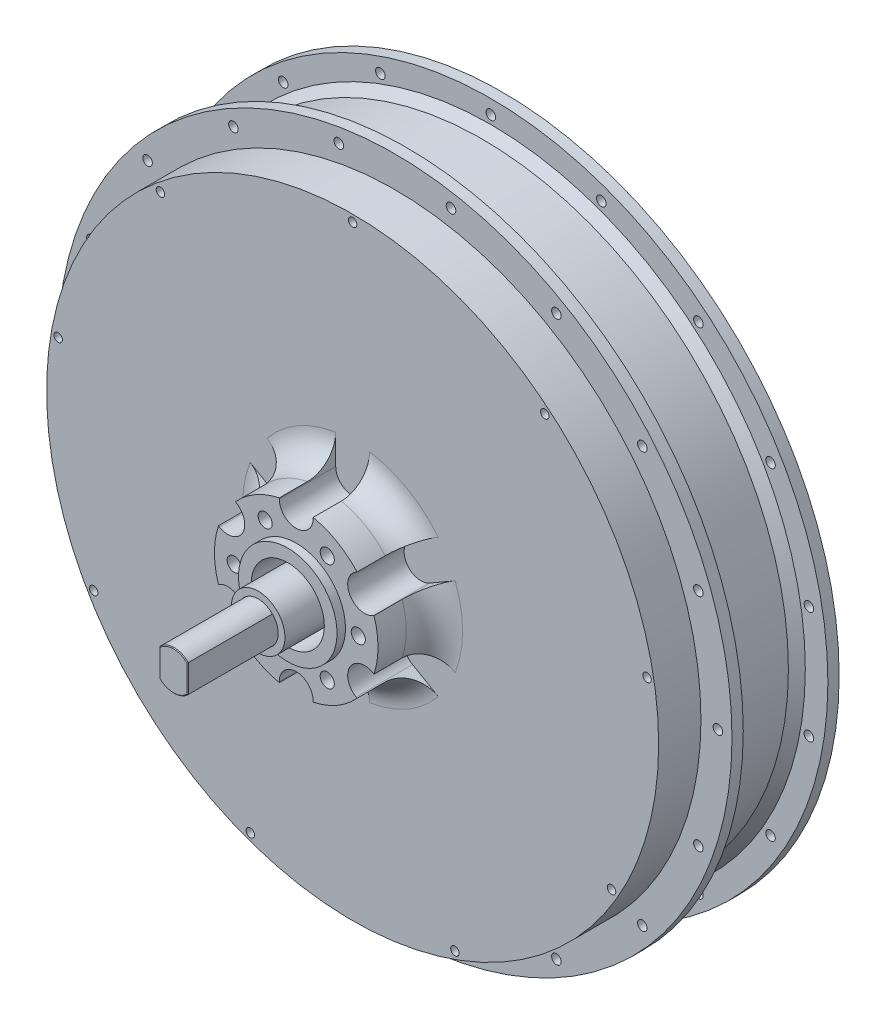
SolidWorks part; units mm, degrees
ref_plane "Front Plane" through (0, 0, 0) normal (0, 0, 1) x (1, 0, 0)
ref_plane "Top Plane" through (0, 0, 0) normal (0, 1, 0) x (1, 0, 0)
ref_plane "Right Plane" through (0, 0, 0) normal (1, 0, 0) x (0, 0, -1)
sketch "Sketch1" plane through (0, 0, 0) normal (0, 0, 1) x (1, 0, 0)
  line L0 (-22.4342, 24.8051) -> (-22.4342, 12.8051) construction
  line L3 (-27.4342, 18.8051) -> (-17.4342, 18.8051) construction
  line L4 (-27.4342, 23.7041) -> (-27.4342, 13.9062)
  line L5 (-17.4342, 23.7041) -> (-17.4342, 13.9062)
  arc A0 (-27.4342, 15.4885) -> (-17.4342, 15.4885) centre (-22.4342, 18.8051) ccw construction
  arc A1 (-17.4342, 22.1218) -> (-27.4342, 22.1218) centre (-22.4342, 18.8051) ccw construction
  arc A2 (-27.4342, 13.9062) -> (-17.4342, 13.9062) centre (-22.4342, 18.8051) ccw
  arc A3 (-17.4342, 23.7041) -> (-27.4342, 23.7041) centre (-22.4342, 18.8051) ccw
  dimension "D1" = 6
extrude "Extrude1" add sketch "Sketch1" against normal blind 195
chamfer "Chamfer1" distance 0.25 angle 45 8 edges at (-22.4342, 11.8051, -195) (-27.4342, 18.8051, -195) (-17.4342, 18.8051, -195) (-22.4342, 25.8051, -195) (-22.4342, 11.8051, 0) (-27.4342, 18.8051, 0) (-17.4342, 18.8051, 0) (-22.4342, 25.8051, 0)
ref_plane "Plane17" through (0, 0, -97.5) normal (0, 0, 1) x (1, 0, 0)
sketch "Sketch18" plane through (0, 0, -97.5) normal (0, 0, 1) x (1, 0, 0)
  line L0 (-22.4342, 25.8051) -> (-22.4342, 11.8051) construction
  line L1 (-27.4342, 18.8051) -> (-17.4342, 18.8051) construction
  line L2 (-27.4342, 13.9062) -> (-27.4342, 23.7041) construction
  line L3 (-17.4342, 23.7041) -> (-17.4342, 13.9062) construction
  arc A0 (-17.4342, 23.7041) -> (-27.4342, 23.7041) centre (-22.4342, 18.8051) ccw construction
  arc A1 (-27.4342, 13.9062) -> (-17.4342, 13.9062) centre (-22.4342, 18.8051) ccw construction
ref_plane "Plane1" through (0, 0, -165) normal (0, 0, -1) x (-1, 0, 0)
sketch "Sketch2" plane through (0, 0, -165) normal (0, 0, -1) x (-1, 0, 0)
  circle A0 centre (22.4342, 18.8051) radius 7.1
  circle A1 centre (22.4342, 18.8051) radius 6.15 construction
  circle A2 centre (22.4342, 18.8051) radius 9.5
  dimension "D1" = 14.2
  dimension "D2" = 19
extrude "Extrude2" add sketch "Sketch2" against normal blind 33.5 separate body
ref_plane "Plane2" through (0, 0, -131.5) normal (0, 0, 1) x (1, 0, 0)
sketch "Sketch3" plane through (0, 0, -131.5) normal (0, 0, 1) x (1, 0, 0)
  circle A0 centre (-22.4342, 18.8051) radius 17.4625
  circle A1 centre (-22.4342, 18.8051) radius 7.1
  dimension "D1" = 34.925
extrude "Extrude3" add sketch "Sketch3" against normal blind 12
ref_plane "Plane4" through (-22.4342, 0, 0) normal (1, 0, 0) x (0, 0, -1)
sketch "Sketch5" plane through (-22.4342, 0, 0) normal (1, 0, 0) x (0, 0, -1)
  line L0 (0, 18.8051) -> (195, 18.8051) construction
  line L1 (109.5, 127.3051) -> (112.5, 130.3051)
  line L2 (78.5, 138.3051) -> (78.5, 127.3051)
  line L3 (131.5, 25.9051) -> (131.5, 50.8051)
  line L4 (120.5, 18.8051) -> (120.5, 50.8051) construction
  line L5 (131.5, 50.8051) -> (131.25, 50.8051)
  line L6 (0, 14.0093) -> (0, 23.601) construction
  line L7 (195, 23.601) -> (195, 14.0093) construction
  line L8 (127.5, 50.8051) -> (127.5, 54.8051) construction
  line L9 (127.5, 18.8051) -> (127.5, 50.8051) construction
  line L11 (63.5, 18.8051) -> (131.5, 18.8051) construction
  line L12 (82.5, 130.3051) -> (82.5, 138.3051)
  line L13 (82.5, 138.3051) -> (78.5, 138.3051)
  line L14 (85.5, 127.3051) -> (82.5, 130.3051)
  line L16 (123.5, 58.5551) -> (123.5, 127.3051)
  line L17 (116.5, 130.2648) -> (116.5, 18.8051) construction
  line L18 (63.5, 127.3051) -> (78.5, 127.3051)
  line L20 (116.5, 138.3051) -> (116.5, 127.3051)
  line L22 (116.5, 127.3051) -> (123.5, 127.3051)
  line L23 (97.5, 18.8051) -> (97.5, 127.3051) construction
  line L24 (63.5, 127.3051) -> (63.5, 57.8051)
  line L27 (63.5, 25.9051) -> (131.5, 25.9051)
  line L28 (131.5, 50.8051) -> (63.5, 50.8051) construction
  line L29 (63.5, 25.9051) -> (63.5, 57.8051) construction
  line L31 (78.5, 130.3051) -> (78.5, 18.8051) construction
  line L32 (43.5, 47.8051) -> (53.5, 47.8051)
  line L33 (123.5, 58.5551) -> (78.5, 58.5551) construction
  line L36 (43.5, 31.7701) -> (63.5, 31.7701)
  line L37 (40.5, 36.2701) -> (40.5, 31.7701)
  line L38 (43.5, 31.7701) -> (40.5, 31.7701)
  line L39 (165, 18.8051) -> (165, 31.995) construction
  line L40 (165, 9.3051) -> (165, 28.3051) construction
  line L41 (85.5, 127.3051) -> (109.5, 127.3051)
  line L42 (143.5, 18.8051) -> (143.5, 40.2887) construction
  line L43 (143.5, 9.3051) -> (143.5, 28.3051) construction
  line L44 (112.5, 130.3051) -> (112.5, 138.3051)
  line L45 (112.5, 138.3051) -> (116.5, 138.3051)
  line L47 (43.5, 36.2701) -> (43.5, 31.7701) construction
  line L48 (43.5, 36.2701) -> (131.5, 36.2701) construction
  line L49 (43.5, 36.2701) -> (43.5, 47.8051)
  line L50 (63.5, 25.9051) -> (63.5, 31.7701)
  line L51 (40.5, 36.2701) -> (43.5, 36.2701)
  arc A0 (131.25, 50.8051) -> (123.5, 58.5551) centre (131.25, 58.5551) cw
  arc A1 (63.5, 57.8051) -> (53.5, 47.8051) centre (53.5, 57.8051) cw
  point P57 (82.5, 127.3051)
  point P58 (112.5, 127.3051)
  dimension "D12" = 23
  dimension "D20" = 4
  dimension "D8" = 7.75
  dimension "D13" = 10
  dimension "D10" = 15
  dimension "D3" = 195
  dimension "D4" = 4
  dimension "D5" = 11
  dimension "D6" = 11
  dimension "D7" = 97.5
  dimension "D9" = 30
  dimension "D11" = 12.965
  dimension "D14" = 21.5
  dimension "D16" = 119.5
  dimension "D18" = 30
  dimension "D19" = 108.5
revolve "Revolve1" add sketch "Sketch5" angle 360 about L0
ref_plane "Plane5" through (0, 0, -116.5) normal (0, 0, -1) x (-1, 0, 0)
sketch "Sketch6" plane through (0, 0, -116.5) normal (0, 0, -1) x (-1, 0, 0)
  line L0 (22.4342, 18.8051) -> (22.4342, 133.3051) construction
  circle A0 centre (22.4342, 18.8051) radius 6.15 construction
  circle A1 centre (61.5955, 126.3999) radius 1.7
  circle A2 centre (22.4342, 18.3051) radius 120 construction
  circle A3 centre (22.4342, 133.3051) radius 1.7
  circle A4 centre (96.0334, 106.5172) radius 1.7
  circle A5 centre (121.5941, 76.0551) radius 1.7
  circle A6 centre (135.1947, 38.6878) radius 1.7
  circle A7 centre (135.1947, -1.0776) radius 1.7
  circle A8 centre (121.5941, -38.4449) radius 1.7
  circle A9 centre (96.0334, -68.907) radius 1.7
  circle A10 centre (61.5955, -88.7897) radius 1.7
  circle A11 centre (22.4342, -95.6949) radius 1.7
  circle A12 centre (-16.7271, -88.7897) radius 1.7
  circle A13 centre (-51.165, -68.907) radius 1.7
  circle A14 centre (-76.7257, -38.4449) radius 1.7
  circle A15 centre (-90.3263, -1.0776) radius 1.7
  circle A16 centre (-90.3263, 38.6878) radius 1.7
  circle A17 centre (-76.7257, 76.0551) radius 1.7
  circle A18 centre (-51.165, 106.5172) radius 1.7
  circle A19 centre (-16.7271, 126.3999) radius 1.7
  circle A21 centre (22.4342, 18.8051) radius 114.5 construction
  dimension "D1" = 18
  dimension "D2" = 229
extrude "Extrude5" cut sketch "Sketch6" against normal blind 4
ref_plane "Plane6" through (0, 0, -78.5) normal (0, 0, 1) x (1, 0, 0)
sketch "Sketch7" plane through (0, 0, -78.5) normal (0, 0, 1) x (1, 0, 0)
  line L0 (-22.4342, 18.8051) -> (-22.4342, 133.3051) construction
  line L1 (-22.4342, 18.8051) -> (-42.3169, 131.5656) construction
  circle A0 centre (-2.5515, 131.5656) radius 1.7
  circle A1 centre (34.8158, 117.965) radius 1.7
  circle A2 centre (65.2779, 92.4043) radius 1.7
  circle A3 centre (85.1606, 57.9664) radius 1.7
  circle A4 centre (92.0658, 18.8051) radius 1.7
  circle A5 centre (85.1606, -20.3562) radius 1.7
  circle A6 centre (65.2779, -54.794) radius 1.7
  circle A7 centre (34.8158, -80.3548) radius 1.7
  circle A8 centre (-2.5515, -93.9554) radius 1.7
  circle A9 centre (-42.3169, -93.9554) radius 1.7
  circle A10 centre (-79.6842, -80.3548) radius 1.7
  circle A11 centre (-110.1463, -54.794) radius 1.7
  circle A12 centre (-130.029, -20.3562) radius 1.7
  circle A13 centre (-136.9342, 18.8051) radius 1.7
  circle A14 centre (-130.029, 57.9664) radius 1.7
  circle A15 centre (-110.1463, 92.4043) radius 1.7
  circle A16 centre (-79.6842, 117.965) radius 1.7
  circle A17 centre (-22.4342, 18.8051) radius 114.5 construction
  circle A19 centre (-42.3169, 131.5656) radius 1.7
  dimension "D1" = 229
  dimension "D3" = 10
  dimension "D2" = 18
extrude "Extrude6" cut sketch "Sketch7" against normal blind 4
ref_plane "Plane18" through (0, 0, -30) normal (0, 0, 1) x (1, 0, 0)
sketch "Sketch19" plane through (0, 0, -30) normal (0, 0, 1) x (1, 0, 0)
  circle A3 centre (-22.4342, 18.8051) radius 9.5
  circle A4 centre (-22.4342, 18.8051) radius 6.15 construction
  circle A5 centre (-22.4342, 18.8051) radius 7.1
  dimension "D3" = 14.2
  dimension "D4" = 19
extrude "Extrude20" add sketch "Sketch19" against normal blind 30
ref_plane "Plane13" through (0, 0, -63.5) normal (0, 0, 1) x (1, 0, 0)
sketch "Sketch14" plane through (0, 0, -63.5) normal (0, 0, 1) x (1, 0, 0)
  line L1 (-22.4342, 18.8051) -> (-22.4342, 124.8051) construction
  circle A0 centre (-22.4342, 18.8051) radius 106 construction
  circle A1 centre (45.7013, 100.0058) radius 1.5
  circle A2 centre (-22.4342, 124.8051) radius 1.5
  circle A3 centre (81.9554, 37.2118) radius 1.5
  circle A4 centre (69.3645, -34.1949) radius 1.5
  circle A5 centre (13.8199, -80.8023) radius 1.5
  circle A6 centre (-58.6883, -80.8023) radius 1.5
  circle A7 centre (-114.2329, -34.1949) radius 1.5
  circle A8 centre (-126.8238, 37.2118) radius 1.5
  circle A9 centre (-90.5697, 100.0058) radius 1.5
extrude "Extrude21" cut sketch "Sketch14" against normal blind 10
ref_plane "Plane19" through (0, 0, -123.5) normal (0, 0, -1) x (-1, 0, 0)
sketch "Sketch20" plane through (0, 0, -123.5) normal (0, 0, -1) x (-1, 0, 0)
  line L1 (22.4342, 18.8051) -> (-46.9869, 101.5379) construction
  line L3 (22.4342, 18.8051) -> (-13.8199, 118.4126) construction
  circle A0 centre (22.4342, 18.8051) radius 106 construction
  circle A1 centre (-13.8199, 118.4126) radius 1.5
  circle A2 centre (58.6883, 118.4126) radius 1.5
  circle A3 centre (114.2329, 71.8051) radius 1.5
  circle A4 centre (126.8238, 0.3984) radius 1.5
  circle A5 centre (90.5697, -62.3956) radius 1.5
  circle A6 centre (22.4342, -87.1949) radius 1.5
  circle A7 centre (-45.7013, -62.3956) radius 1.5
  circle A8 centre (-81.9554, 0.3984) radius 1.5
  circle A9 centre (-69.3645, 71.8051) radius 1.5
  dimension "D2" = 20
extrude "Extrude22" cut sketch "Sketch20" against normal blind 10
ref_plane "Plane20" through (0, 0, -63.5) normal (0, 0, 1) x (1, 0, 0)
sketch "Sketch21" plane through (0, 0, -63.5) normal (0, 0, 1) x (1, 0, 0)
  line L0 (-22.4342, 18.8051) -> (-22.4342, 40.8051) construction
  line L2 (-2.2776, 15.0688) -> (-0.7538, 15.0688) construction
  line L3 (-9.1201, 34.3931) -> (-8.3582, 35.7127) construction
  line L4 (-15.5917, 38.1295) -> (-14.8298, 39.4491) construction
  line L5 (-2.2776, 22.5415) -> (-0.7538, 22.5415) construction
  line L6 (-15.5917, -0.5192) -> (-14.8298, -1.8388) construction
  line L7 (-9.1201, 3.2172) -> (-8.3582, 1.8975) construction
  line L8 (-35.7483, 3.2172) -> (-36.5102, 1.8975) construction
  line L9 (-29.2767, -0.5192) -> (-30.0386, -1.8388) construction
  line L10 (-42.5908, 22.5415) -> (-44.1146, 22.5415) construction
  line L11 (-42.5908, 15.0688) -> (-44.1146, 15.0688) construction
  line L12 (-29.2767, 38.1295) -> (-30.0386, 39.4491) construction
  line L13 (-22.4342, 18.8051) -> (-11.4342, 37.8577) construction
  line L14 (-35.7483, 34.3931) -> (-36.5102, 35.7127) construction
  circle A0 centre (-22.4342, 18.8051) radius 22 construction
  arc A1 (-0.7538, 15.0688) -> (-0.7538, 22.5415) centre (-0.4342, 18.8051) ccw construction
  arc A2 (-8.3582, 35.7127) -> (-14.8298, 39.4491) centre (-11.4342, 37.8577) ccw construction
  circle A3 centre (-0.4342, 18.8051) radius 2.5 construction
  arc A4 (-14.8298, -1.8388) -> (-8.3582, 1.8975) centre (-11.4342, -0.2474) ccw construction
  circle A5 centre (-11.4342, -0.2474) radius 2.5 construction
  arc A6 (-36.5102, 1.8975) -> (-30.0386, -1.8388) centre (-33.4342, -0.2474) ccw construction
  circle A7 centre (-33.4342, -0.2474) radius 2.5 construction
  arc A8 (-44.1146, 22.5415) -> (-44.1146, 15.0688) centre (-44.4342, 18.8051) ccw construction
  circle A9 centre (-44.4342, 18.8051) radius 2.5 construction
  arc A10 (-30.0386, 39.4491) -> (-36.5102, 35.7127) centre (-33.4342, 37.8577) ccw construction
  circle A11 centre (-33.4342, 37.8577) radius 2.5 construction
  arc A12 (-35.7483, 34.3931) -> (-42.5908, 22.5415) centre (-22.4342, 18.8051) ccw construction
  arc A13 (-15.5917, 38.1295) -> (-29.2767, 38.1295) centre (-22.4342, 18.8051) ccw construction
  arc A14 (-2.2776, 22.5415) -> (-9.1201, 34.3931) centre (-22.4342, 18.8051) ccw construction
  arc A15 (-9.1201, 3.2172) -> (-2.2776, 15.0688) centre (-22.4342, 18.8051) ccw construction
  circle A16 centre (-11.4342, 37.8577) radius 2.5 construction
  arc A17 (-29.2767, -0.5192) -> (-15.5917, -0.5192) centre (-22.4342, 18.8051) ccw construction
  arc A18 (-42.5908, 15.0688) -> (-35.7483, 3.2172) centre (-22.4342, 18.8051) ccw construction
  circle A19 centre (-22.4342, 18.8051) radius 22 construction
  dimension "D1" = 44
  dimension "D2" = 30
ref_plane "Plane21" through (0, 0, -63.5) normal (0, 0, 1) x (1, 0, 0)
sketch "Sketch22" plane through (0, 0, -63.5) normal (0, 0, 1) x (1, 0, 0)
  line L0 (-22.4342, 18.8051) -> (-22.4342, 138.3051) construction
  line L1 (-22.4342, 33.8051) -> (-22.4342, 40.8051) construction
  line L2 (-1.1855, 38.0013) -> (8.5959, 43.6486)
  line L3 (4.8145, 27.609) -> (14.5959, 33.2563)
  line L4 (4.8145, 10.0013) -> (14.5959, 4.354)
  line L5 (-1.1855, -0.391) -> (8.5959, -6.0383)
  line L6 (-16.4342, -9.1949) -> (-16.4342, -20.4894)
  line L7 (-28.4342, -9.1949) -> (-28.4342, -20.4894)
  line L8 (-43.6829, -0.391) -> (-53.4643, -6.0383)
  line L9 (-49.6829, 10.0013) -> (-59.4643, 4.354)
  line L10 (-49.6829, 27.609) -> (-59.4643, 33.2563)
  line L11 (-43.6829, 38.0013) -> (-53.4643, 43.6486)
  line L13 (-28.4342, 46.8051) -> (-28.4342, 58.0997)
  line L14 (-16.4342, 46.8051) -> (-16.4342, 58.0997)
  circle A1 centre (-22.4342, 18.8051) radius 15 construction
  arc A2 (-16.4342, 58.0997) -> (-28.4342, 58.0997) centre (-22.4342, 18.8051) ccw
  arc A3 (14.5959, 33.2563) -> (8.5959, 43.6486) centre (-22.4342, 18.8051) ccw
  circle A4 centre (-22.4342, 18.8051) radius 17.465 construction
  arc A5 (-1.1855, 38.0013) -> (4.8145, 27.609) centre (1.8145, 32.8051) ccw
  arc A6 (8.5959, -6.0383) -> (14.5959, 4.354) centre (-22.4342, 18.8051) ccw
  arc A7 (4.8145, 10.0013) -> (-1.1855, -0.391) centre (1.8145, 4.8051) ccw
  arc A8 (-28.4342, -20.4894) -> (-16.4342, -20.4894) centre (-22.4342, 18.8051) ccw
  arc A9 (-16.4342, -9.1949) -> (-28.4342, -9.1949) centre (-22.4342, -9.1949) ccw
  arc A10 (-59.4643, 4.354) -> (-53.4643, -6.0383) centre (-22.4342, 18.8051) ccw
  arc A11 (-43.6829, -0.391) -> (-49.6829, 10.0013) centre (-46.6829, 4.8051) ccw
  arc A12 (-53.4643, 43.6486) -> (-59.4643, 33.2563) centre (-22.4342, 18.8051) ccw
  arc A13 (-49.6829, 27.609) -> (-43.6829, 38.0013) centre (-46.6829, 32.8051) ccw
  circle A14 centre (-22.4342, 18.8051) radius 119.5 construction
  circle A15 centre (-22.4342, 18.8051) radius 22 construction
  arc A17 (-28.4342, 46.8051) -> (-16.4342, 46.8051) centre (-22.4342, 46.8051) ccw
  dimension "D1" = 7
extrude "Extrude23" cut sketch "Sketch22" along normal blind 21
ref_plane "Plane22" through (0, 0, -43.5) normal (0, 0, 1) x (1, 0, 0)
sketch "Sketch23" plane through (0, 0, -43.5) normal (0, 0, 1) x (1, 0, 0)
  circle A0 centre (-22.4342, 18.8051) radius 22 construction
  circle A1 centre (-33.4342, 37.8577) radius 2.5
  circle A2 centre (-11.4342, 37.8577) radius 2.5
  circle A3 centre (-0.4342, 18.8051) radius 2.5
  circle A4 centre (-11.4342, -0.2474) radius 2.5
  circle A5 centre (-33.4342, -0.2474) radius 2.5
  circle A6 centre (-44.4342, 18.8051) radius 2.5
extrude "Extrude24" cut sketch "Sketch23" against normal blind 12
ref_plane "Plane23" through (0, 0, -97.5) normal (0, 0, 1) x (1, 0, 0)
sketch "Sketch24" plane through (0, 0, -97.5) normal (0, 0, 1) x (1, 0, 0)
  line L0 (-22.4342, 133.3051) -> (-22.4342, -95.6949) construction
  line L1 (-136.9342, 18.8051) -> (92.0658, 18.8051) construction
  circle A0 centre (-22.4342, 18.8051) radius 114.5 construction
  dimension "D1" = 229
